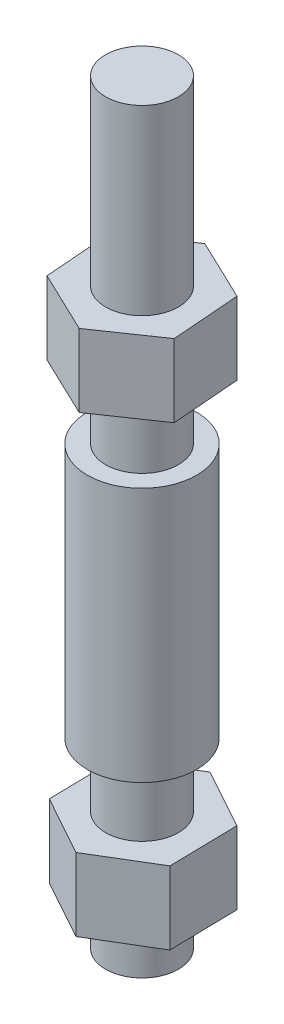
SolidWorks part; units mm, degrees
ref_plane "Ön Düzlem" through (0, 0, 0) normal (0, 0, 1) x (1, 0, 0)
ref_plane "Üst Düzlem" through (0, 0, 0) normal (0, 1, 0) x (1, 0, 0)
ref_plane "Sağ Düzlem" through (0, 0, 0) normal (1, 0, 0) x (0, 0, -1)
sketch "Çizim1" plane through (0, 0, 0) normal (0, 1, 0) x (1, 0, 0)
  circle A0 centre (0, 0) radius 4
  dimension "D1" = 8
extrude "Yükseklik-Ekstrüzyon1" add sketch "Çizim1" along normal blind 20
sketch "Çizim2" plane through (0, 20, 0) normal (0, 1, 0) x (1, 0, 0)
  circle A0 centre (0, 0) radius 6
  dimension "D1" = 12
extrude "Yükseklik-Ekstrüzyon2" add sketch "Çizim2" along normal blind 28
sketch "Çizim3" plane through (0, 48, 0) normal (0, 1, 0) x (1, 0, 0)
  circle A0 centre (0, 0) radius 4
  dimension "D1" = 8
extrude "Yükseklik-Ekstrüzyon3" add sketch "Çizim3" along normal blind 35
sketch "Çizim4" plane through (0, 0, 0) normal (0, -1, 0) x (1, 0, 0)
  line L1 (-6.3083, 3.8723) -> (-6.447, -3.632)
  line L2 (-6.447, -3.632) -> (-0.0175, -7.5043)
  line L3 (-0.0175, -7.5043) -> (6.5507, -3.8723)
  line L4 (6.5507, -3.8723) -> (6.6895, 3.632)
  line L5 (6.6895, 3.632) -> (0.26, 7.5043)
  line L6 (0.26, 7.5043) -> (-6.3083, 3.8723)
  circle A0 centre (0.1212, 0) radius 6.5 construction
  dimension "D1" = 13
extrude "Yükseklik-Ekstrüzyon4" add sketch "Çizim4" against normal blind 8 from offset 5 offset against normal yes
sketch "Çizim5" plane through (0, 83, 0) normal (0, 1, 0) x (1, 0, 0)
  line L1 (6.7734, -3.2333) -> (6.1869, 4.2493)
  line L2 (6.1869, 4.2493) -> (-0.5865, 7.4826)
  line L3 (-0.5865, 7.4826) -> (-6.7734, 3.2333)
  line L4 (-6.7734, 3.2333) -> (-6.1869, -4.2493)
  line L5 (-6.1869, -4.2493) -> (0.5865, -7.4826)
  line L6 (0.5865, -7.4826) -> (6.7734, -3.2333)
  circle A0 centre (0, 0) radius 6.5 construction
  dimension "D1" = 13
extrude "Yükseklik-Ekstrüzyon5" add sketch "Çizim5" against normal blind 8 from offset 20
